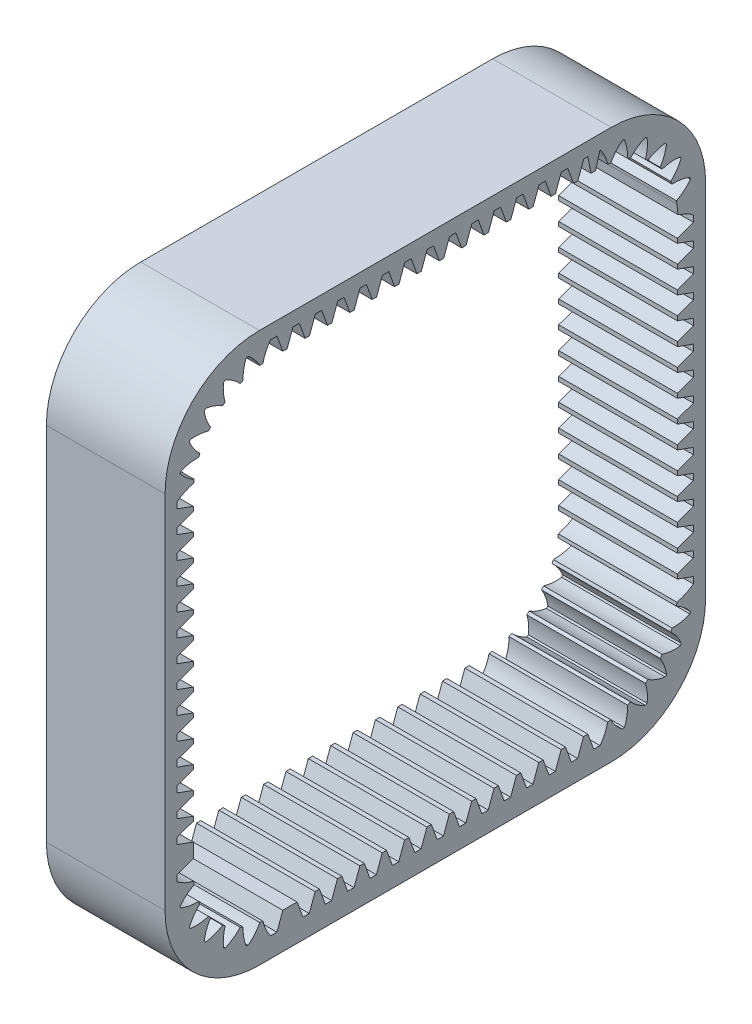
SolidWorks part; units mm, degrees
ref_plane "前视基准面" through (0, 0, 0) normal (0, 0, 1) x (1, 0, 0)
ref_plane "上视基准面" through (0, 0, 0) normal (0, 1, 0) x (1, 0, 0)
ref_plane "右视基准面" through (0, 0, 0) normal (1, 0, 0) x (0, 0, -1)
other "Configuration Table"
sketch "草图2" plane through (0, 0, 0) normal (1, 0, 0) x (0, 0, -1)
  line L0 (19.4215, -19.4215) -> (21.75, -21.75) construction
  line L1 (13.8828, -21.75) -> (21.75, -21.75) construction
  line L2 (21.75, -13.8) -> (21.75, -21.75) construction
  line L3 (-13.3477, -21.75) -> (-13.7172, -21.75) construction
  line L4 (21.7529, 14.3917) -> (21.75, -13.7172) construction
  line L5 (21.75, -13.8828) -> (21.75, -21.75) construction
  line L6 (20.3598, 14.5276) -> (20.4497, 13.7168)
  line L7 (20.4006, 12.0156) -> (20.4006, 11.6479)
  line L8 (20.4006, 10.1307) -> (20.4006, 9.763)
  line L9 (20.4006, 8.2457) -> (20.4006, 7.878)
  line L10 (20.4006, 6.3608) -> (20.4006, 5.993)
  line L11 (20.4006, 4.4758) -> (20.4006, 4.1081)
  line L12 (20.4006, 2.5909) -> (20.4006, 2.2231)
  line L13 (20.4006, 0.7059) -> (20.4006, 0.3382)
  line L14 (20.4006, -1.1791) -> (20.4006, -1.5468)
  line L15 (20.4006, -3.064) -> (20.4006, -3.4317)
  line L16 (20.4006, -4.949) -> (20.4006, -5.3167)
  line L17 (20.4006, -6.8339) -> (20.4006, -7.2016)
  line L18 (20.4006, -8.7189) -> (20.4006, -9.0866)
  line L19 (20.4006, -10.6038) -> (20.4006, -10.9716)
  line L20 (20.4006, -12.4888) -> (20.4006, -12.8565)
  line L21 (21.7506, -13.8824) -> (21.7506, -13.3479)
  line L22 (21.7506, -13.3479) -> (20.4006, -12.8565)
  line L23 (20.4006, -12.4888) -> (21.7506, -11.9974)
  line L24 (21.7506, -11.9974) -> (21.7506, -11.4629)
  line L25 (21.7506, -11.4629) -> (20.4006, -10.9716)
  line L26 (20.4006, -10.6038) -> (21.7506, -10.1125)
  line L27 (21.7506, -10.1125) -> (21.7506, -9.578)
  line L28 (21.7506, -9.578) -> (20.4006, -9.0866)
  line L29 (20.4006, -8.7189) -> (21.7506, -8.2275)
  line L30 (21.7506, -8.2275) -> (21.7506, -7.693)
  line L31 (21.7506, -7.693) -> (20.4006, -7.2016)
  line L32 (20.4006, -6.8339) -> (21.7506, -6.3426)
  line L33 (21.7506, -6.3426) -> (21.7506, -5.808)
  line L34 (21.7506, -5.808) -> (20.4006, -5.3167)
  line L35 (20.4006, -4.949) -> (21.7506, -4.4576)
  line L36 (21.7506, -4.4576) -> (21.7506, -3.9231)
  line L37 (21.7506, -3.9231) -> (20.4006, -3.4317)
  line L38 (20.4006, -3.064) -> (21.7506, -2.5727)
  line L39 (21.7506, -2.5727) -> (21.7506, -2.0381)
  line L40 (21.7506, -2.0381) -> (20.4006, -1.5468)
  line L41 (20.4006, -1.1791) -> (21.7506, -0.6877)
  line L42 (21.7506, -0.6877) -> (21.7506, -0.1532)
  line L43 (21.7506, -0.1532) -> (20.4006, 0.3382)
  line L44 (20.4006, 0.7059) -> (21.7506, 1.1973)
  line L45 (21.7506, 1.1973) -> (21.7506, 1.7318)
  line L46 (21.7506, 1.7318) -> (20.4006, 2.2231)
  line L47 (20.4006, 2.5909) -> (21.7506, 3.0822)
  line L48 (21.7506, 3.0822) -> (21.7506, 3.6167)
  line L49 (21.7506, 3.6167) -> (20.4006, 4.1081)
  line L50 (20.4006, 4.4758) -> (21.7506, 4.9672)
  line L51 (21.7506, 4.9672) -> (21.7506, 5.5017)
  line L52 (-12.8565, -20.4006) -> (-12.0156, -20.4006)
  line L53 (-2.35, 0) -> (2.7, 0) construction
  line L54 (-12.5068, -21.7501) -> (-12.507, -21.7506)
  line L55 (-11.1566, -21.7506) -> (-11.6479, -20.4006)
  line L56 (-10.622, -21.7506) -> (-11.1566, -21.7506)
  line L57 (-10.1307, -20.4006) -> (-10.622, -21.7506)
  line L58 (-9.2716, -21.7506) -> (-9.763, -20.4006)
  line L59 (-8.7371, -21.7506) -> (-9.2716, -21.7506)
  line L60 (-8.2457, -20.4006) -> (-8.7371, -21.7506)
  line L61 (-7.3866, -21.7506) -> (-7.878, -20.4006)
  line L62 (-6.8521, -21.7506) -> (-7.3866, -21.7506)
  line L63 (-6.3608, -20.4006) -> (-6.8521, -21.7506)
  line L64 (-5.5017, -21.7506) -> (-5.993, -20.4006)
  line L65 (-4.9672, -21.7506) -> (-5.5017, -21.7506)
  line L66 (-4.4758, -20.4006) -> (-4.9672, -21.7506)
  line L67 (-3.6167, -21.7506) -> (-4.1081, -20.4006)
  line L68 (-3.0822, -21.7506) -> (-3.6167, -21.7506)
  line L69 (-2.5909, -20.4006) -> (-3.0822, -21.7506)
  line L70 (-1.7318, -21.7506) -> (-2.2231, -20.4006)
  line L71 (-1.1973, -21.7506) -> (-1.7318, -21.7506)
  line L72 (-0.7059, -20.4006) -> (-1.1973, -21.7506)
  line L73 (0.1532, -21.7506) -> (-0.3382, -20.4006)
  line L74 (0.6877, -21.7506) -> (0.1532, -21.7506)
  line L75 (1.1791, -20.4006) -> (0.6877, -21.7506)
  line L76 (2.0381, -21.7506) -> (1.5468, -20.4006)
  line L77 (2.5727, -21.7506) -> (2.0381, -21.7506)
  line L78 (3.064, -20.4006) -> (2.5727, -21.7506)
  line L79 (3.9231, -21.7506) -> (3.4317, -20.4006)
  line L80 (4.4576, -21.7506) -> (3.9231, -21.7506)
  line L81 (4.949, -20.4006) -> (4.4576, -21.7506)
  line L82 (5.808, -21.7506) -> (5.3167, -20.4006)
  line L83 (6.3426, -21.7506) -> (5.808, -21.7506)
  line L84 (6.8339, -20.4006) -> (6.3426, -21.7506)
  line L85 (7.693, -21.7506) -> (7.2016, -20.4006)
  line L86 (8.2275, -21.7506) -> (7.693, -21.7506)
  line L87 (8.7189, -20.4006) -> (8.2275, -21.7506)
  line L88 (9.578, -21.7506) -> (9.0866, -20.4006)
  line L89 (10.1125, -21.7506) -> (9.578, -21.7506)
  line L90 (10.6038, -20.4006) -> (10.1125, -21.7506)
  line L91 (11.4629, -21.7506) -> (10.9716, -20.4006)
  line L92 (11.9974, -21.7506) -> (11.4629, -21.7506)
  line L93 (12.4888, -20.4006) -> (11.9974, -21.7506)
  line L94 (13.3479, -21.7506) -> (12.8565, -20.4006)
  line L95 (13.8824, -21.7506) -> (13.3479, -21.7506)
  line L96 (12.4888, -20.4006) -> (12.8565, -20.4006)
  line L97 (10.6038, -20.4006) -> (10.9716, -20.4006)
  line L98 (8.7189, -20.4006) -> (9.0866, -20.4006)
  line L99 (6.8339, -20.4006) -> (7.2016, -20.4006)
  line L100 (4.949, -20.4006) -> (5.3167, -20.4006)
  line L101 (3.064, -20.4006) -> (3.4317, -20.4006)
  line L102 (1.1791, -20.4006) -> (1.5468, -20.4006)
  line L103 (-0.7059, -20.4006) -> (-0.3382, -20.4006)
  line L104 (-2.5909, -20.4006) -> (-2.2231, -20.4006)
  line L105 (-4.4758, -20.4006) -> (-4.1081, -20.4006)
  line L106 (-6.3608, -20.4006) -> (-5.993, -20.4006)
  line L107 (-8.2457, -20.4006) -> (-7.878, -20.4006)
  line L108 (-10.1307, -20.4006) -> (-9.763, -20.4006)
  line L109 (-12.0156, -20.4006) -> (-11.6479, -20.4006)
  line L110 (21.75, -21.75) -> (-8.1785, 8.1785) construction
  line L111 (21.7506, 5.5017) -> (20.4006, 5.993)
  line L112 (20.4006, 6.3608) -> (21.7506, 6.8521)
  line L113 (21.7506, 6.8521) -> (21.7506, 7.3866)
  line L114 (21.7506, 7.3866) -> (20.4006, 7.878)
  line L115 (20.4006, 8.2457) -> (21.7506, 8.7371)
  line L116 (21.7506, 8.7371) -> (21.7506, 9.2716)
  line L117 (21.7506, 9.2716) -> (20.4006, 9.763)
  line L118 (20.4006, 10.1307) -> (21.7506, 10.622)
  line L119 (21.7506, 10.622) -> (21.7506, 11.1566)
  line L120 (21.7506, 11.1566) -> (20.4006, 11.6479)
  line L121 (20.4006, 12.0156) -> (21.7506, 12.507)
  line L122 (21.7506, 12.507) -> (21.7506, 13.0415)
  line L123 (21.7506, 13.0415) -> (21.3278, 13.3429)
  line L124 (21.7286, 14.3829) -> (21.7529, 14.3917)
  line L125 (-21.75, 21.75) -> (-21.75, -13.7172) construction
  line L126 (14.3917, -21.7529) -> (-12.5068, -21.7501) construction
  line L127 (0, -21.7514) -> (13.7172, -21.75) construction
  line L128 (-21.75, -13.8828) -> (-21.75, -21.75) construction
  line L129 (-21.7529, 14.3917) -> (-21.75, -13.7172) construction
  line L130 (-21.75, -13.8) -> (-21.75, -21.75) construction
  line L131 (-13.8828, -21.75) -> (-21.75, -21.75) construction
  line L132 (-19.4215, -19.4215) -> (-21.75, -21.75) construction
  line L133 (-13.8824, -21.7506) -> (-13.3479, -21.7506)
  line L134 (-13.3479, -21.7506) -> (-12.8565, -20.4006)
  line L135 (-21.7506, -13.3479) -> (-20.4006, -12.8565)
  line L136 (-21.7506, -13.8824) -> (-21.7506, -13.3479)
  line L137 (-14.3829, -21.7286) -> (-14.3917, -21.7529)
  line L138 (21.75, 21.75) -> (13.8, 21.75) construction
  line L139 (0, -24.6752) -> (0, 24.1552) construction
  line L140 (-21.7514, 0) -> (-21.75, 13.7172) construction
  line L141 (-21.7529, 14.3917) -> (-21.7501, -12.5068) construction
  line L142 (-13.8828, 21.75) -> (-21.75, 21.75) construction
  line L143 (0, 21.7514) -> (-13.7172, 21.75) construction
  line L144 (-21.75, -13.3477) -> (-21.75, -13.7172) construction
  line L145 (-13.8, 21.75) -> (-21.75, 21.75) construction
  line L146 (-21.75, 13.8828) -> (-21.75, 21.75) construction
  line L147 (-19.4215, 19.4215) -> (-21.75, 21.75) construction
  line L148 (-21.7506, -13.3479) -> (-20.4006, -12.8565)
  line L149 (-21.7506, -13.8824) -> (-21.7506, -13.3479)
  line L150 (13.8, 21.75) -> (21.75, 21.75) construction
  line L151 (12.8565, 21.7506) -> (13.1261, 20.4006)
  line L152 (12.507, 21.7506) -> (12.8565, 21.7506)
  line L153 (12.0156, 20.4006) -> (12.507, 21.7506)
  line L154 (11.1566, 21.7506) -> (11.6479, 20.4006)
  line L155 (10.622, 21.7506) -> (11.1566, 21.7506)
  line L156 (10.1307, 20.4006) -> (10.622, 21.7506)
  line L157 (9.2716, 21.7506) -> (9.763, 20.4006)
  line L158 (8.7371, 21.7506) -> (9.2716, 21.7506)
  line L159 (8.2457, 20.4006) -> (8.7371, 21.7506)
  line L160 (7.3866, 21.7506) -> (7.878, 20.4006)
  line L161 (6.8521, 21.7506) -> (7.3866, 21.7506)
  line L162 (6.3608, 20.4006) -> (6.8521, 21.7506)
  line L163 (5.5017, 21.7506) -> (5.993, 20.4006)
  line L164 (-20.4006, -12.0156) -> (-20.4006, -11.6479)
  line L165 (-20.4006, -10.1307) -> (-20.4006, -9.763)
  line L166 (-20.4006, -8.2457) -> (-20.4006, -7.878)
  line L167 (-20.4006, -6.3608) -> (-20.4006, -5.993)
  line L168 (-20.4006, -4.4758) -> (-20.4006, -4.1081)
  line L169 (-20.4006, -2.5909) -> (-20.4006, -2.2231)
  line L170 (-20.4006, -0.7059) -> (-20.4006, -0.3382)
  line L171 (-20.4006, 1.1791) -> (-20.4006, 1.5468)
  line L172 (-20.4006, 3.064) -> (-20.4006, 3.4317)
  line L173 (-20.4006, 4.949) -> (-20.4006, 5.3167)
  line L174 (-20.4006, 6.8339) -> (-20.4006, 7.2016)
  line L175 (-20.4006, 8.7189) -> (-20.4006, 9.0866)
  line L176 (-20.4006, 10.6038) -> (-20.4006, 10.9716)
  line L177 (-20.4006, 12.4888) -> (-20.4006, 12.8565)
  line L178 (-21.7506, 13.8824) -> (-21.7506, 13.3479)
  line L179 (-21.7506, 13.3479) -> (-20.4006, 12.8565)
  line L180 (-20.4006, 12.4888) -> (-21.7506, 11.9974)
  line L181 (-21.7506, 11.9974) -> (-21.7506, 11.4629)
  line L182 (-21.7506, 11.4629) -> (-20.4006, 10.9716)
  line L183 (-20.4006, 10.6038) -> (-21.7506, 10.1125)
  line L184 (-21.7506, 10.1125) -> (-21.7506, 9.578)
  line L185 (-21.7506, 9.578) -> (-20.4006, 9.0866)
  line L186 (-20.4006, 8.7189) -> (-21.7506, 8.2275)
  line L187 (-21.7506, 8.2275) -> (-21.7506, 7.693)
  line L188 (-21.7506, 7.693) -> (-20.4006, 7.2016)
  line L189 (-20.4006, 6.8339) -> (-21.7506, 6.3426)
  line L190 (-21.7506, 6.3426) -> (-21.7506, 5.808)
  line L191 (-21.7506, 5.808) -> (-20.4006, 5.3167)
  line L192 (-20.4006, 4.949) -> (-21.7506, 4.4576)
  line L193 (-21.7506, 4.4576) -> (-21.7506, 3.9231)
  line L194 (-21.7506, 3.9231) -> (-20.4006, 3.4317)
  line L195 (-20.4006, 3.064) -> (-21.7506, 2.5727)
  line L196 (-21.7506, 2.5727) -> (-21.7506, 2.0381)
  line L197 (-21.7506, 2.0381) -> (-20.4006, 1.5468)
  line L198 (-20.4006, 1.1791) -> (-21.7506, 0.6877)
  line L199 (-21.7506, 0.6877) -> (-21.7506, 0.1532)
  line L200 (-21.7506, 0.1532) -> (-20.4006, -0.3382)
  line L201 (-20.4006, -0.7059) -> (-21.7506, -1.1973)
  line L202 (-21.7506, -1.1973) -> (-21.7506, -1.7318)
  line L203 (-21.7506, -1.7318) -> (-20.4006, -2.2231)
  line L204 (-20.4006, -2.5909) -> (-21.7506, -3.0822)
  line L205 (-21.7506, -3.0822) -> (-21.7506, -3.6167)
  line L206 (-21.7506, -3.6167) -> (-20.4006, -4.1081)
  line L207 (-20.4006, -4.4758) -> (-21.7506, -4.9672)
  line L208 (-21.7506, -4.9672) -> (-21.7506, -5.5017)
  line L209 (-21.7506, -5.5017) -> (-20.4006, -5.993)
  line L210 (-20.4006, -6.3608) -> (-21.7506, -6.8521)
  line L211 (-21.7506, -6.8521) -> (-21.7506, -7.3866)
  line L212 (-21.7506, -7.3866) -> (-20.4006, -7.878)
  line L213 (-20.4006, -8.2457) -> (-21.7506, -8.7371)
  line L214 (-21.7506, -8.7371) -> (-21.7506, -9.2716)
  line L215 (-21.7506, -9.2716) -> (-20.4006, -9.763)
  line L216 (-20.4006, -10.1307) -> (-21.7506, -10.622)
  line L217 (-21.7506, -10.622) -> (-21.7506, -11.1566)
  line L218 (-21.7506, -11.1566) -> (-20.4006, -11.6479)
  line L219 (-21.7501, -12.5068) -> (-21.7506, -12.507)
  line L220 (-20.4006, -12.8565) -> (-20.4006, -12.0156)
  line L221 (4.9672, 21.7506) -> (5.5017, 21.7506)
  line L222 (4.4758, 20.4006) -> (4.9672, 21.7506)
  line L223 (3.6167, 21.7506) -> (4.1081, 20.4006)
  line L224 (3.0822, 21.7506) -> (3.6167, 21.7506)
  line L225 (2.5909, 20.4006) -> (3.0822, 21.7506)
  line L226 (1.7318, 21.7506) -> (2.2231, 20.4006)
  line L227 (1.1973, 21.7506) -> (1.7318, 21.7506)
  line L228 (0.7059, 20.4006) -> (1.1973, 21.7506)
  line L229 (-0.1532, 21.7506) -> (0.3382, 20.4006)
  line L230 (-0.6877, 21.7506) -> (-0.1532, 21.7506)
  line L231 (-1.1791, 20.4006) -> (-0.6877, 21.7506)
  line L232 (-2.0381, 21.7506) -> (-1.5468, 20.4006)
  line L233 (-2.5727, 21.7506) -> (-2.0381, 21.7506)
  line L234 (-3.064, 20.4006) -> (-2.5727, 21.7506)
  line L235 (-3.9231, 21.7506) -> (-3.4317, 20.4006)
  line L236 (-4.4576, 21.7506) -> (-3.9231, 21.7506)
  line L237 (-4.949, 20.4006) -> (-4.4576, 21.7506)
  line L238 (-5.808, 21.7506) -> (-5.3167, 20.4006)
  line L239 (-6.3426, 21.7506) -> (-5.808, 21.7506)
  line L240 (-6.8339, 20.4006) -> (-6.3426, 21.7506)
  line L241 (-7.693, 21.7506) -> (-7.2016, 20.4006)
  line L242 (-8.2275, 21.7506) -> (-7.693, 21.7506)
  line L243 (-8.7189, 20.4006) -> (-8.2275, 21.7506)
  line L244 (-9.578, 21.7506) -> (-9.0866, 20.4006)
  line L245 (-10.1125, 21.7506) -> (-9.578, 21.7506)
  line L246 (-10.6038, 20.4006) -> (-10.1125, 21.7506)
  line L247 (-11.4629, 21.7506) -> (-10.9716, 20.4006)
  line L248 (-11.9974, 21.7506) -> (-11.4629, 21.7506)
  line L249 (-12.4888, 20.4006) -> (-11.9974, 21.7506)
  line L250 (-13.3479, 21.7506) -> (-12.8565, 20.4006)
  line L251 (-13.8824, 21.7506) -> (-13.3479, 21.7506)
  line L252 (-12.4888, 20.4006) -> (-12.8565, 20.4006)
  line L253 (-10.6038, 20.4006) -> (-10.9716, 20.4006)
  line L254 (-8.7189, 20.4006) -> (-9.0866, 20.4006)
  line L255 (-6.8339, 20.4006) -> (-7.2016, 20.4006)
  line L256 (-4.949, 20.4006) -> (-5.3167, 20.4006)
  line L257 (-3.064, 20.4006) -> (-3.4317, 20.4006)
  line L258 (-1.1791, 20.4006) -> (-1.5468, 20.4006)
  line L259 (0.7059, 20.4006) -> (0.3382, 20.4006)
  line L260 (2.5909, 20.4006) -> (2.2231, 20.4006)
  line L261 (4.4758, 20.4006) -> (4.1081, 20.4006)
  line L262 (6.3608, 20.4006) -> (5.993, 20.4006)
  line L263 (8.2457, 20.4006) -> (7.878, 20.4006)
  line L264 (10.1307, 20.4006) -> (9.763, 20.4006)
  line L265 (12.0156, 20.4006) -> (11.6479, 20.4006)
  line L266 (14.3829, 21.7286) -> (14.3917, 21.7529)
  line L267 (13.1261, 20.4006) -> (13.4976, 20.4006)
  line L268 (19.4215, 19.4215) -> (21.75, 21.75) construction
  line L269 (21.75, 13.8828) -> (21.75, 21.75) construction
  line L270 (13.8, 21.75) -> (21.75, 21.75) construction
  line L271 (13.8828, 21.75) -> (21.75, 21.75) construction
  line L272 (21.75, 13.3477) -> (21.75, 13.7172) construction
  line L273 (12.8566, 21.75) -> (-13.7172, 21.75) construction
  line L274 (12.5068, 21.7501) -> (12.507, 21.7506)
  line L275 (13.4976, 20.4006) -> (13.8832, 21.7496)
  line L276 (13.3479, 21.7506) -> (13.3429, 21.7368)
  line L277 (21.7286, 14.3829) -> (21.7529, 14.3917)
  line L278 (12.8566, 21.75) -> (12.8565, 21.7506)
  line L279 (13.3479, 21.7506) -> (13.3429, 21.7368)
  line L280 (21.7506, 13.3479) -> (21.7368, 13.3429)
  line L281 (21.7506, 13.8824) -> (21.7506, 13.3479)
  line L282 (21.3278, 13.3429) -> (20.4497, 13.7168)
  line L283 (22.7781, -23.4211) -> (-22.7781, -23.4211)
  line L284 (22.7781, -23.4211) -> (22.7781, 22.9011)
  line L285 (22.7781, 22.9011) -> (-22.7781, 22.9011)
  line L286 (-22.7781, -23.4211) -> (-22.7781, 22.9011)
  line L287 (22.7781, -23.4211) -> (-22.7781, 22.9011) construction
  line L288 (22.7781, 22.9011) -> (-22.7781, -23.4211) construction
  line L319 (-24.6752, 0) -> (24.1552, 0) construction
  line L320 (-21.75, 21.75) -> (12.8566, 21.75) construction
  line L321 (-21.75, 21.75) -> (-21.75, -13.8) construction
  line L323 (21.75, 21.75) -> (21.75, -13.7172) construction
  line L324 (-21.75, 21.75) -> (8.1785, -8.1785) construction
  line L325 (-20.8933, -20.8933) -> (21.75, 21.75) construction
  line L326 (0, -2.35) -> (0, 2.7) construction
  arc A97 (13.8832, -21.7496) -> (21.75, -13.8) centre (13.8, -13.8) ccw construction
  arc A98 (13.8, 21.75) -> (12.4657, 21.6372) centre (13.8, 13.8) cw construction
  circle A100 centre (-13.8, 13.8) radius 7.95 construction
  arc A149 (13.7168, -21.7496) -> (13.7176, -21.7506) centre (16.5859, -19.575) ccw
  arc A151 (13.8824, -21.7506) -> (14.5276, -20.3598) centre (11.0141, -19.575) ccw
  arc A152 (14.5276, -20.3598) -> (14.795, -20.3246) centre (13.8, -13.8) ccw
  arc A153 (14.795, -20.3246) -> (15.7782, -21.501) centre (17.9856, -18.6572) ccw
  arc A154 (15.7782, -21.501) -> (15.9373, -21.4583) centre (13.8, -13.8) ccw
  arc A155 (15.9373, -21.4583) -> (16.2006, -19.9479) centre (12.6037, -20.0992) ccw
  arc A156 (16.2006, -19.9479) -> (16.4498, -19.8447) centre (13.8, -13.8) ccw
  arc A157 (16.4498, -19.8447) -> (17.7039, -20.7266) centre (19.1001, -17.4084) ccw
  arc A158 (17.7039, -20.7266) -> (17.8466, -20.6442) centre (13.8, -13.8) ccw
  arc A159 (17.8466, -20.6442) -> (17.71, -19.1172) centre (14.2749, -20.1942) ccw
  arc A160 (17.71, -19.1172) -> (17.924, -18.9529) centre (13.8, -13.8) ccw
  arc A161 (17.924, -18.9529) -> (19.3636, -19.4802) centre (19.8534, -15.9136) ccw
  arc A162 (19.3636, -19.4802) -> (19.4802, -19.3636) centre (13.8, -13.8) ccw
  arc A163 (19.4802, -19.3636) -> (18.9529, -17.924) centre (15.9136, -19.8534) ccw
  arc A164 (18.9529, -17.924) -> (19.1172, -17.71) centre (13.8, -13.8) ccw
  arc A165 (19.1172, -17.71) -> (20.6442, -17.8466) centre (20.1942, -14.2749) ccw
  arc A166 (20.6442, -17.8466) -> (20.7266, -17.7039) centre (13.8, -13.8) ccw
  arc A167 (20.7266, -17.7039) -> (19.8447, -16.4498) centre (17.4084, -19.1001) ccw
  arc A168 (19.8447, -16.4498) -> (19.948, -16.2006) centre (13.8, -13.8) ccw
  arc A169 (19.948, -16.2006) -> (21.4583, -15.9373) centre (20.0992, -12.6037) ccw
  arc A170 (21.4583, -15.9373) -> (21.501, -15.7782) centre (13.8, -13.8) ccw
  arc A171 (21.501, -15.7782) -> (20.3246, -14.795) centre (18.6572, -17.9856) ccw
  arc A172 (20.3246, -14.795) -> (20.3598, -14.5276) centre (13.8, -13.8) ccw
  arc A173 (20.3598, -14.5276) -> (21.7506, -13.8824) centre (19.575, -11.0141) ccw
  arc A175 (21.7506, -13.7176) -> (21.7496, -13.7168) centre (19.575, -16.5859) ccw
  arc A197 (21.7496, -13.7168) -> (13.7168, -21.7496) centre (13.8, -13.8) ccw construction
  arc A198 (-17.7742, -20.6854) -> (-12.4657, -21.6372) centre (-13.8, -13.8) cw construction
  arc A199 (20.6854, 17.7742) -> (13.8, 21.75) centre (13.8, 13.8) ccw construction
  arc A200 (21.7496, -13.8832) -> (13.8, -21.75) centre (13.8, -13.8) cw construction
  arc A201 (21.7506, -13.8824) -> (20.3598, -14.5276) centre (19.575, -11.0141) cw
  arc A202 (21.7496, -13.7168) -> (21.7506, -13.7176) centre (19.575, -16.5859) cw
  arc A203 (-21.7496, -13.8832) -> (-13.8, -21.75) centre (-13.8, -13.8) ccw construction
  arc A204 (-21.7496, -13.7168) -> (-12.4657, -21.6372) centre (-13.8, -13.8) cw construction
  arc A205 (-13.8832, -21.7496) -> (-21.75, -13.8) centre (-13.8, -13.8) cw construction
  arc A206 (-21.7496, -13.7168) -> (-21.7506, -13.7176) centre (-19.575, -16.5859) ccw
  arc A207 (-21.7506, -13.8824) -> (-20.3598, -14.5276) centre (-19.575, -11.0141) ccw
  arc A208 (-21.7506, -13.7176) -> (-21.7496, -13.7168) centre (-19.575, -16.5859) cw
  arc A209 (-20.3598, -14.5276) -> (-21.7506, -13.8824) centre (-19.575, -11.0141) cw
  arc A210 (-20.3246, -14.795) -> (-20.3598, -14.5276) centre (-13.8, -13.8) cw
  arc A211 (-21.501, -15.7782) -> (-20.3246, -14.795) centre (-18.6572, -17.9856) cw
  arc A212 (-21.4583, -15.9373) -> (-21.501, -15.7782) centre (-13.8, -13.8) cw
  arc A213 (-19.948, -16.2006) -> (-21.4583, -15.9373) centre (-20.0992, -12.6037) cw
  arc A214 (-19.8447, -16.4498) -> (-19.948, -16.2006) centre (-13.8, -13.8) cw
  arc A215 (-20.7266, -17.7039) -> (-19.8447, -16.4498) centre (-17.4084, -19.1001) cw
  arc A216 (-20.6442, -17.8466) -> (-20.7266, -17.7039) centre (-13.8, -13.8) cw
  arc A217 (-19.1172, -17.71) -> (-20.6442, -17.8466) centre (-20.1942, -14.2749) cw
  arc A218 (-18.9529, -17.924) -> (-19.1172, -17.71) centre (-13.8, -13.8) cw
  arc A219 (-19.4802, -19.3636) -> (-18.9529, -17.924) centre (-15.9136, -19.8534) cw
  arc A220 (-19.3636, -19.4802) -> (-19.4802, -19.3636) centre (-13.8, -13.8) cw
  arc A221 (-17.924, -18.9529) -> (-19.3636, -19.4802) centre (-19.8534, -15.9136) cw
  arc A222 (-17.71, -19.1172) -> (-17.924, -18.9529) centre (-13.8, -13.8) cw
  arc A223 (-17.8466, -20.6442) -> (-17.71, -19.1172) centre (-14.2749, -20.1942) cw
  arc A224 (-17.7039, -20.7266) -> (-17.8466, -20.6442) centre (-13.8, -13.8) cw
  arc A225 (-16.4498, -19.8447) -> (-17.7039, -20.7266) centre (-19.1001, -17.4084) cw
  arc A226 (-16.2006, -19.9479) -> (-16.4498, -19.8447) centre (-13.8, -13.8) cw
  arc A227 (-15.9373, -21.4583) -> (-16.2006, -19.9479) centre (-12.6037, -20.0992) cw
  arc A228 (-15.7782, -21.501) -> (-15.9373, -21.4583) centre (-13.8, -13.8) cw
  arc A229 (-14.795, -20.3246) -> (-15.7782, -21.501) centre (-17.9856, -18.6572) cw
  arc A230 (-14.5276, -20.3598) -> (-14.795, -20.3246) centre (-13.8, -13.8) cw
  arc A231 (-13.8824, -21.7506) -> (-14.5276, -20.3598) centre (-11.0141, -19.575) cw
  arc A232 (-13.7168, -21.7496) -> (-13.7176, -21.7506) centre (-16.5859, -19.575) cw
  arc A233 (-13.3429, -21.7368) -> (-13.7168, -21.7496) centre (-13.8, -13.8) cw construction
  arc A234 (-13.3429, -21.7368) -> (-14.3839, -21.7285) centre (-13.8, -13.8) cw construction
  arc A235 (-21.7368, -13.3429) -> (-21.7285, -14.3839) centre (-13.8, -13.8) ccw construction
  arc A236 (-21.7368, -13.3429) -> (-21.7496, -13.7168) centre (-13.8, -13.8) ccw construction
  arc A237 (-13.7168, -21.7496) -> (-21.6372, -12.4657) centre (-13.8, -13.8) ccw construction
  arc A238 (-13.8832, 21.7496) -> (-21.75, 13.8) centre (-13.8, 13.8) ccw construction
  arc A239 (17.7742, 20.6854) -> (12.4657, 21.6372) centre (13.8, 13.8) cw construction
  arc A240 (-20.6854, -17.7742) -> (-21.6372, -12.4657) centre (-13.8, -13.8) ccw construction
  arc A241 (-13.7168, 21.7496) -> (-21.7496, 13.7168) centre (-13.8, 13.8) cw construction
  circle A242 centre (13.8, -13.8) radius 7.95 construction
  arc A243 (-21.7496, 13.8832) -> (-13.8, 21.75) centre (-13.8, 13.8) cw construction
  arc A244 (-13.7168, 21.7496) -> (-13.7176, 21.7506) centre (-16.5859, 19.575) ccw
  arc A245 (-13.8824, 21.7506) -> (-14.5276, 20.3598) centre (-11.0141, 19.575) ccw
  arc A246 (-13.7176, 21.7506) -> (-13.7168, 21.7496) centre (-16.5859, 19.575) cw
  arc A247 (-14.5276, 20.3598) -> (-13.8824, 21.7506) centre (-11.0141, 19.575) cw
  arc A248 (-14.795, 20.3246) -> (-14.5276, 20.3598) centre (-13.8, 13.8) cw
  arc A249 (-15.7782, 21.501) -> (-14.795, 20.3246) centre (-17.9856, 18.6572) cw
  arc A250 (-15.9373, 21.4583) -> (-15.7782, 21.501) centre (-13.8, 13.8) cw
  arc A251 (-16.2006, 19.948) -> (-15.9373, 21.4583) centre (-12.6037, 20.0992) cw
  arc A252 (-16.4498, 19.8447) -> (-16.2006, 19.948) centre (-13.8, 13.8) cw
  arc A253 (-17.7039, 20.7266) -> (-16.4498, 19.8447) centre (-19.1001, 17.4084) cw
  arc A254 (-17.8466, 20.6442) -> (-17.7039, 20.7266) centre (-13.8, 13.8) cw
  arc A255 (-17.71, 19.1172) -> (-17.8466, 20.6442) centre (-14.2749, 20.1942) cw
  arc A256 (-17.924, 18.9529) -> (-17.71, 19.1172) centre (-13.8, 13.8) cw
  arc A257 (-19.3636, 19.4802) -> (-17.924, 18.9529) centre (-19.8534, 15.9136) cw
  arc A258 (-19.4802, 19.3636) -> (-19.3636, 19.4802) centre (-13.8, 13.8) cw
  arc A259 (-18.9529, 17.924) -> (-19.4802, 19.3636) centre (-15.9136, 19.8534) cw
  arc A260 (-19.1172, 17.71) -> (-18.9529, 17.924) centre (-13.8, 13.8) cw
  arc A261 (-20.6442, 17.8466) -> (-19.1172, 17.71) centre (-20.1942, 14.2749) cw
  arc A262 (-20.7266, 17.7039) -> (-20.6442, 17.8466) centre (-13.8, 13.8) cw
  arc A263 (-19.8447, 16.4498) -> (-20.7266, 17.7039) centre (-17.4084, 19.1001) cw
  arc A264 (-19.9479, 16.2006) -> (-19.8447, 16.4498) centre (-13.8, 13.8) cw
  arc A265 (-21.4583, 15.9373) -> (-19.9479, 16.2006) centre (-20.0992, 12.6037) cw
  arc A266 (-21.501, 15.7782) -> (-21.4583, 15.9373) centre (-13.8, 13.8) cw
  arc A267 (-20.3246, 14.795) -> (-21.501, 15.7782) centre (-18.6572, 17.9856) cw
  arc A268 (-20.3598, 14.5276) -> (-20.3246, 14.795) centre (-13.8, 13.8) cw
  arc A269 (-21.7506, 13.8824) -> (-20.3598, 14.5276) centre (-19.575, 11.0141) cw
  arc A270 (-21.7496, 13.7168) -> (-21.7506, 13.7176) centre (-19.575, 16.5859) cw
  arc A272 (13.8, 21.75) -> (14.3839, 21.7285) centre (13.8, 13.8) cw construction
  arc A273 (21.7368, 13.3429) -> (21.7285, 14.3839) centre (13.8, 13.8) ccw construction
  arc A274 (21.7368, 13.3429) -> (21.7496, 13.7168) centre (13.8, 13.8) ccw construction
  arc A275 (21.7496, 13.8832) -> (13.8, 21.75) centre (13.8, 13.8) ccw construction
  arc A276 (13.8832, 21.7496) -> (21.75, 13.8) centre (13.8, 13.8) cw construction
  arc A277 (21.7496, 13.7168) -> (21.7506, 13.7176) centre (19.575, 16.5859) ccw
  arc A278 (21.7506, 13.8824) -> (21.7496, 13.8832) centre (19.575, 11.0141) ccw
  arc A279 (20.3598, 14.5276) -> (20.3246, 14.795) centre (13.8, 13.8) ccw
  arc A280 (20.3246, 14.795) -> (21.501, 15.7782) centre (18.6572, 17.9856) ccw
  arc A281 (21.501, 15.7782) -> (21.4583, 15.9373) centre (13.8, 13.8) ccw
  arc A282 (21.4583, 15.9373) -> (19.9479, 16.2006) centre (20.0992, 12.6037) ccw
  arc A283 (19.9479, 16.2006) -> (19.8447, 16.4498) centre (13.8, 13.8) ccw
  arc A284 (19.8447, 16.4498) -> (20.7266, 17.7039) centre (17.4084, 19.1001) ccw
  arc A285 (20.7266, 17.7039) -> (20.6442, 17.8466) centre (13.8, 13.8) ccw
  arc A286 (20.6442, 17.8466) -> (19.1172, 17.71) centre (20.1942, 14.2749) ccw
  arc A287 (19.1172, 17.71) -> (18.9529, 17.924) centre (13.8, 13.8) ccw
  arc A288 (18.9529, 17.924) -> (19.4802, 19.3636) centre (15.9136, 19.8534) ccw
  arc A289 (19.4802, 19.3636) -> (19.3636, 19.4802) centre (13.8, 13.8) ccw
  arc A290 (19.3636, 19.4802) -> (17.924, 18.9529) centre (19.8534, 15.9136) ccw
  arc A291 (17.924, 18.9529) -> (17.71, 19.1172) centre (13.8, 13.8) ccw
  arc A292 (17.71, 19.1172) -> (17.8466, 20.6442) centre (14.2749, 20.1942) ccw
  arc A293 (17.8466, 20.6442) -> (17.7039, 20.7266) centre (13.8, 13.8) ccw
  arc A294 (17.7039, 20.7266) -> (16.4498, 19.8447) centre (19.1001, 17.4084) ccw
  arc A295 (16.4498, 19.8447) -> (16.2006, 19.948) centre (13.8, 13.8) ccw
  arc A296 (16.2006, 19.948) -> (15.9373, 21.4583) centre (12.6037, 20.0992) ccw
  arc A297 (15.9373, 21.4583) -> (15.7782, 21.501) centre (13.8, 13.8) ccw
  arc A298 (15.7782, 21.501) -> (14.795, 20.3246) centre (17.9856, 18.6572) ccw
  arc A299 (14.795, 20.3246) -> (14.5276, 20.3598) centre (13.8, 13.8) ccw
  arc A300 (14.5276, 20.3598) -> (13.8824, 21.7506) centre (11.0141, 19.575) ccw
  arc A301 (13.7176, 21.7506) -> (13.7168, 21.7496) centre (16.5859, 19.575) ccw
  arc A302 (13.8824, 21.7506) -> (14.5276, 20.3598) centre (11.0141, 19.575) cw
  arc A303 (13.7168, 21.7496) -> (13.7176, 21.7506) centre (16.5859, 19.575) cw
  arc A304 (12.4657, 21.6372) -> (21.7285, 14.3839) centre (13.8, 13.8) ccw construction
  arc A305 (13.8, 21.75) -> (14.3839, 21.7285) centre (13.8, 13.8) cw construction
  point P16 (21.3278, 13.3429)
  point P466 (0, 0)
  point P497 (0, -0.26)
  dimension "D3" = 15.9
  dimension "D1" = 43.5
  dimension "D2" = 43.5
extrude "凸台-拉伸1" add sketch "草图2" along normal blind 10
fillet "圆角1" radius 7.95 4 edges at (5, 22.9011, 22.7781) (5, -23.4211, 22.7781) (5, -23.4211, -22.7781) (5, 22.9011, -22.7781)
